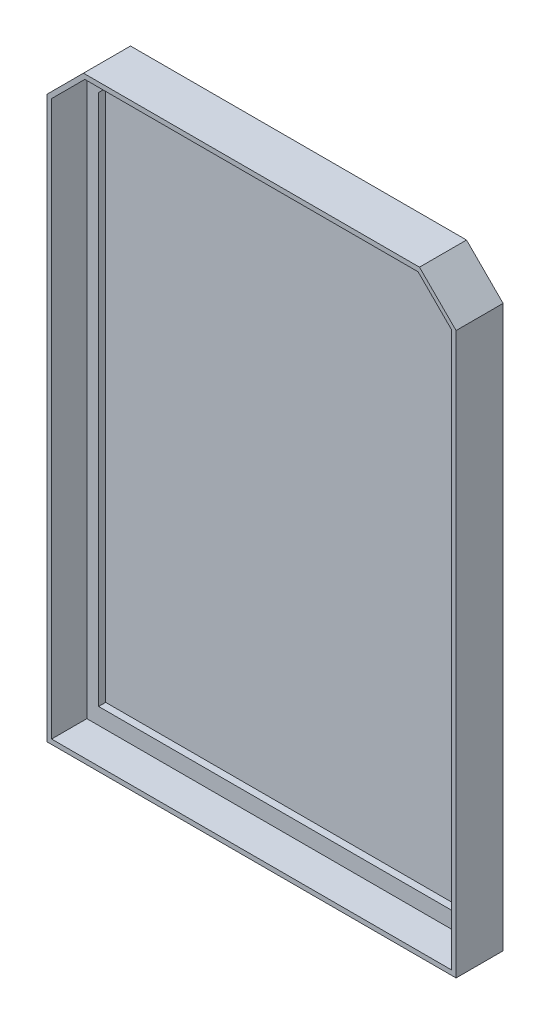
SolidWorks part; units mm, degrees
ref_plane "Front Plane" through (0, 0, 0) normal (1, 0, 0) x (0, 1, 0)
ref_plane "Top Plane" through (0, 0, 0) normal (0, 0, 1) x (0, 1, 0)
ref_plane "Right Plane" through (0, 0, 0) normal (0, 1, 0) x (-1, 0, 0)
sketch "Sketch1" plane through (0, 0, 0) normal (0, 0, 1) x (0, 1, 0)
  line L0 (54.0503, 40) -> (59, 35.0503)
  line L1 (-62.5, -42.5) -> (62.5, -42.5) construction
  line L2 (-62.5, -42.5) -> (-62.5, 42.5)
  line L3 (-62.5, 42.5) -> (62.5, 42.5) construction
  line L4 (62.5, -42.5) -> (62.5, 42.5) construction
  line L5 (-62.5, -42.5) -> (62.5, 42.5) construction
  line L6 (-62.5, 42.5) -> (62.5, -42.5) construction
  line L7 (-59, -40) -> (59, -40) construction
  line L8 (-59, -40) -> (-59, 40)
  line L9 (-59, 40) -> (59, 40) construction
  line L10 (59, -40) -> (59, 40) construction
  line L11 (-59, -40) -> (59, 40) construction
  line L12 (-59, 40) -> (59, -40) construction
  line L13 (-63.5, -43.5) -> (63.5, -43.5) construction
  line L14 (-63.5, -43.5) -> (-63.5, 43.5)
  line L15 (-63.5, 43.5) -> (63.5, 43.5) construction
  line L16 (63.5, -43.5) -> (63.5, 43.5) construction
  line L17 (-63.5, -43.5) -> (63.5, 43.5) construction
  line L18 (-63.5, 43.5) -> (63.5, -43.5) construction
  line L19 (-59, 40) -> (54.0503, 40)
  line L20 (59, 35.0503) -> (59, -40) construction
  line L21 (59, -35.0503) -> (54.0503, -40)
  line L22 (59, -35.0503) -> (59, 35.0503)
  line L23 (54.0503, -40) -> (-59, -40)
  line L24 (55.4289, 42.5) -> (62.5, 35.4289)
  line L25 (62.5, -35.4289) -> (55.4289, -42.5)
  line L26 (55.4289, -42.5) -> (-62.5, -42.5)
  line L27 (62.5, -35.4289) -> (62.5, 35.4289)
  line L28 (55.4289, 42.5) -> (-62.5, 42.5)
  line L29 (55.7218, 43.5) -> (63.5, 35.7218)
  line L30 (63.5, -35.7218) -> (55.7218, -43.5)
  line L31 (55.7218, -43.5) -> (-63.5, -43.5)
  line L32 (63.5, -35.7218) -> (63.5, 35.7218)
  line L33 (55.7218, 43.5) -> (-63.5, 43.5)
  point P0 (0, 0)
  point P5 (0, 0)
  point P11 (0, 0)
  dimension "D1" = 85
  dimension "D2" = 125
  dimension "D3" = 118
  dimension "D4" = 80
  dimension "D5" = 87
  dimension "D6" = 127
  dimension "D7" = 7
  dimension "D8" = 45
  dimension "D9" = 7
  dimension "D10" = 45
  dimension "D11" = 10
  dimension "D12" = 10
  dimension "D13" = 11
  dimension "D14" = 11
extrude "Boss-Extrude1" add sketch "Sketch1" along normal blind 1.5 contours L1 L4 L3 L2 L10 L7 L8 L9
sketch "Sketch2" plane through (0, 0, 0) normal (0, 0, 1) x (0, 1, 0)
  line L4 (55.7218, 43.5) -> (-63.5, 43.5)
  line L5 (55.7218, 43.5) -> (-63.5, 43.5)
  line L6 (63.5, 35.7218) -> (55.7218, 43.5)
  line L7 (-63.5, 43.5) -> (-63.5, -43.5)
  line L11 (-63.5, 43.5) -> (-63.5, -43.5)
  line L12 (54.0503, 40) -> (-59, 40)
  line L13 (54.0503, 40) -> (-59, 40)
  line L14 (59, 35.0503) -> (54.0503, 40)
  line L15 (-59, 40) -> (-59, -40)
  line L19 (-59, 40) -> (-59, -40) construction
  line L20 (55.4289, 42.5) -> (-62.5, 42.5)
  line L21 (55.4289, 42.5) -> (-62.5, 42.5)
  line L22 (62.5, 35.4289) -> (55.4289, 42.5)
  line L23 (-62.5, 42.5) -> (-62.5, -42.5)
  line L27 (-62.5, 42.5) -> (-62.5, -42.5)
  line L30 (59, 35.0503) -> (54.0503, 40)
  line L31 (59, -35.0503) -> (59, 35.0503)
  line L32 (59, -35.0503) -> (59, 35.0503)
  line L33 (54.0503, -40) -> (59, -35.0503)
  line L34 (54.0503, -40) -> (59, -35.0503)
  line L35 (-59, -40) -> (54.0503, -40)
  line L36 (-59, -40) -> (54.0503, -40)
  line L37 (62.5, 35.4289) -> (55.4289, 42.5)
  line L38 (62.5, -35.4289) -> (62.5, 35.4289)
  line L39 (62.5, -35.4289) -> (62.5, 35.4289)
  line L40 (55.4289, -42.5) -> (62.5, -35.4289)
  line L41 (55.4289, -42.5) -> (62.5, -35.4289)
  line L42 (-62.5, -42.5) -> (55.4289, -42.5)
  line L43 (-62.5, -42.5) -> (55.4289, -42.5)
  line L44 (63.5, 35.7218) -> (55.7218, 43.5)
  line L45 (63.5, -35.7218) -> (63.5, 35.7218)
  line L46 (63.5, -35.7218) -> (63.5, 35.7218)
  line L47 (55.7218, -43.5) -> (63.5, -35.7218)
  line L48 (55.7218, -43.5) -> (63.5, -35.7218)
  line L49 (-63.5, -43.5) -> (55.7218, -43.5)
  line L50 (-63.5, -43.5) -> (55.7218, -43.5)
  dimension "D1" = 0
  dimension "D2" = 0
  dimension "D3" = 0
extrude "Boss-Extrude2" add sketch "Sketch2" along normal blind 9 contours L11 L50 L48 L46 L44 L5 L43 L27 L21 L37 L39 L41
sketch "Sketch3" plane through (0, 0, 0) normal (0, 0, 1) x (0, 1, 0)
  line L4 (55.7218, 43.5) -> (-63.5, 43.5)
  line L5 (55.7218, 43.5) -> (-63.5, 43.5)
  line L6 (63.5, 35.7218) -> (55.7218, 43.5)
  line L7 (-63.5, 43.5) -> (-63.5, -43.5)
  line L11 (-63.5, 43.5) -> (-63.5, -43.5)
  line L12 (54.0503, 40) -> (-59, 40)
  line L13 (54.0503, 40) -> (-59, 40)
  line L14 (59, 35.0503) -> (54.0503, 40)
  line L15 (-59, 40) -> (-59, -40)
  line L19 (-59, 40) -> (-59, -40) construction
  line L20 (55.4289, 42.5) -> (-62.5, 42.5)
  line L21 (55.4289, 42.5) -> (-62.5, 42.5)
  line L22 (62.5, 35.4289) -> (55.4289, 42.5)
  line L23 (-62.5, 42.5) -> (-62.5, -42.5)
  line L27 (-62.5, 42.5) -> (-62.5, -42.5) construction
  line L30 (59, 35.0503) -> (54.0503, 40)
  line L31 (59, -35.0503) -> (59, 35.0503)
  line L32 (59, -35.0503) -> (59, 35.0503)
  line L33 (54.0503, -40) -> (59, -35.0503)
  line L34 (54.0503, -40) -> (59, -35.0503)
  line L35 (-59, -40) -> (54.0503, -40)
  line L36 (-59, -40) -> (54.0503, -40)
  line L37 (62.5, 35.4289) -> (55.4289, 42.5)
  line L38 (62.5, -35.4289) -> (62.5, 35.4289)
  line L39 (62.5, -35.4289) -> (62.5, 35.4289)
  line L40 (55.4289, -42.5) -> (62.5, -35.4289)
  line L41 (55.4289, -42.5) -> (62.5, -35.4289)
  line L42 (-62.5, -42.5) -> (55.4289, -42.5)
  line L43 (-62.5, -42.5) -> (55.4289, -42.5)
  line L44 (63.5, 35.7218) -> (55.7218, 43.5)
  line L45 (63.5, -35.7218) -> (63.5, 35.7218)
  line L46 (63.5, -35.7218) -> (63.5, 35.7218)
  line L47 (55.7218, -43.5) -> (63.5, -35.7218)
  line L48 (55.7218, -43.5) -> (63.5, -35.7218)
  line L49 (-63.5, -43.5) -> (55.7218, -43.5)
  line L50 (-63.5, -43.5) -> (55.7218, -43.5)
  dimension "D1" = 0
  dimension "D2" = 0
  dimension "D3" = 0
extrude "Boss-Extrude3" add sketch "Sketch3" against normal blind 1
sketch "Sketch4" plane through (0, 0, -1) normal (0, 0, -1) x (1, 0, 0)
  circle A0 centre (0, 0) radius 6
  circle A1 centre (0, 0) radius 4.25
  dimension "D1" = 8.5
  dimension "D2" = 12
extrude "Boss-Extrude4" add sketch "Sketch4" along normal blind 30
fillet "Fillet1" radius 20 1 edges at (6, 0, -1)
